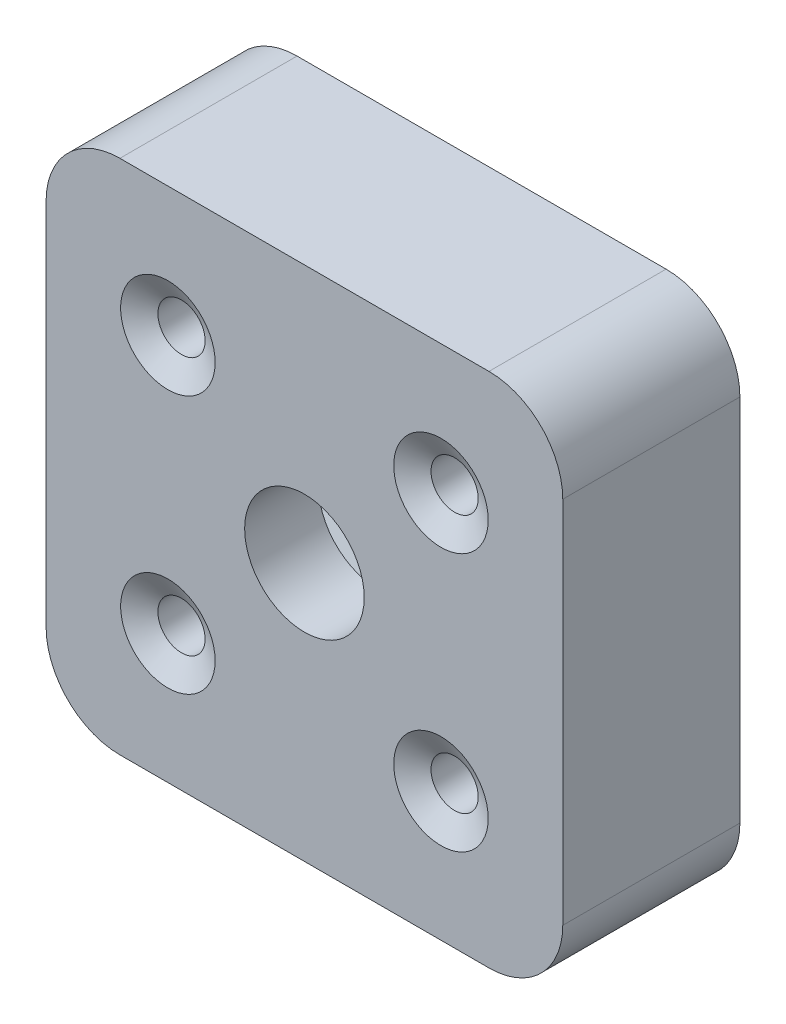
SolidWorks part; units mm, degrees
ref_plane "Front Plane" through (0, 0, 0) normal (0, 0, 1) x (1, 0, 0)
ref_plane "Top Plane" through (0, 0, 0) normal (0, 1, 0) x (1, 0, 0)
ref_plane "Right Plane" through (0, 0, 0) normal (1, 0, 0) x (0, 0, -1)
sketch "Sketch1" plane through (0, 0, 0) normal (0, 0, 1) x (1, 0, 0)
  line L1 (-17.5, -17.5) -> (17.5, -17.5)
  line L2 (-17.5, -17.5) -> (-17.5, 17.5)
  line L3 (-17.5, 17.5) -> (17.5, 17.5)
  line L4 (17.5, -17.5) -> (17.5, 17.5)
  line L5 (-17.5, -17.5) -> (17.5, 17.5) construction
  line L6 (-17.5, 17.5) -> (17.5, -17.5) construction
  line L7 (-9.25, -8.75) -> (9.25, -8.75)
  line L8 (-9.25, -8.75) -> (-9.25, 8.75)
  line L9 (-9.25, 8.75) -> (9.25, 8.75)
  line L10 (9.25, -8.75) -> (9.25, 8.75)
  line L11 (-9.25, -8.75) -> (9.25, 8.75) construction
  line L12 (-9.25, 8.75) -> (9.25, -8.75) construction
  circle A0 centre (0, 0) radius 4.05
  circle A1 centre (-9.25, 8.75) radius 1.6
  circle A2 centre (9.25, 8.75) radius 1.6
  circle A3 centre (-9.25, -8.75) radius 1.6
  circle A4 centre (9.25, -8.75) radius 1.6
  point P0 (0, 0)
  dimension "D3" = 8.1
  dimension "D6" = 3.2
  dimension "D7" = 3.2
  dimension "D8" = 3.2
  dimension "D9" = 3.2
  dimension "D1" = 35
  dimension "D2" = 35
  dimension "D4" = 18.5
  dimension "D5" = 17.5
extrude "Boss-Extrude1" add sketch "Sketch1" along normal blind 12 contours L1 L4 L3 L2 A4 L7 A3 L8 A1 L9 A2 L10 | A4 L10 A2 L9 A1 L8 A3 L7 A0
fillet "Fillet1" radius 5 4 edges at (17.5, -17.5, 6) (-17.5, -17.5, 6) (-17.5, 17.5, 6) (17.5, 17.5, 6)
sketch "Sketch5" plane through (0, 0, 12) normal (0, 0, 1) x (1, 0, 0)
  circle A0 centre (-9.25, 8.75) radius 3.2
  circle A1 centre (9.25, 8.75) radius 3.2
  circle A2 centre (-9.25, -8.75) radius 3.2
  circle A3 centre (9.25, -8.75) radius 3.2
  dimension "D1" = 6.4
  dimension "D2" = 6.4
  dimension "D3" = 6.4
  dimension "D4" = 6.4
extrude "Cut-Extrude1" cut sketch "Sketch5" against normal blind 1 draft 60
sketch "Sketch6" plane through (0, 0, 0) normal (0, 0, -1) x (-1, 0, 0)
  line L0 (0, 0) -> (5, 0) construction
  line L1 (0, 0) -> (6.5385, 3.775) construction
  line L2 (6.5385, 3.775) -> (0, 7.55)
  line L3 (0, 7.55) -> (-6.5385, 3.775)
  line L4 (-6.5385, 3.775) -> (-6.5385, -3.775)
  line L5 (-6.5385, -3.775) -> (0, -7.55)
  line L6 (0, -7.55) -> (6.5385, -3.775)
  line L7 (6.5385, -3.775) -> (6.5385, 3.775)
  circle A0 centre (0, 0) radius 7.55 construction
  dimension "D2" = 15.1
  dimension "D1" = 5
  dimension "D3" = 30
extrude "Cut-Extrude2" cut sketch "Sketch6" against normal blind 7
